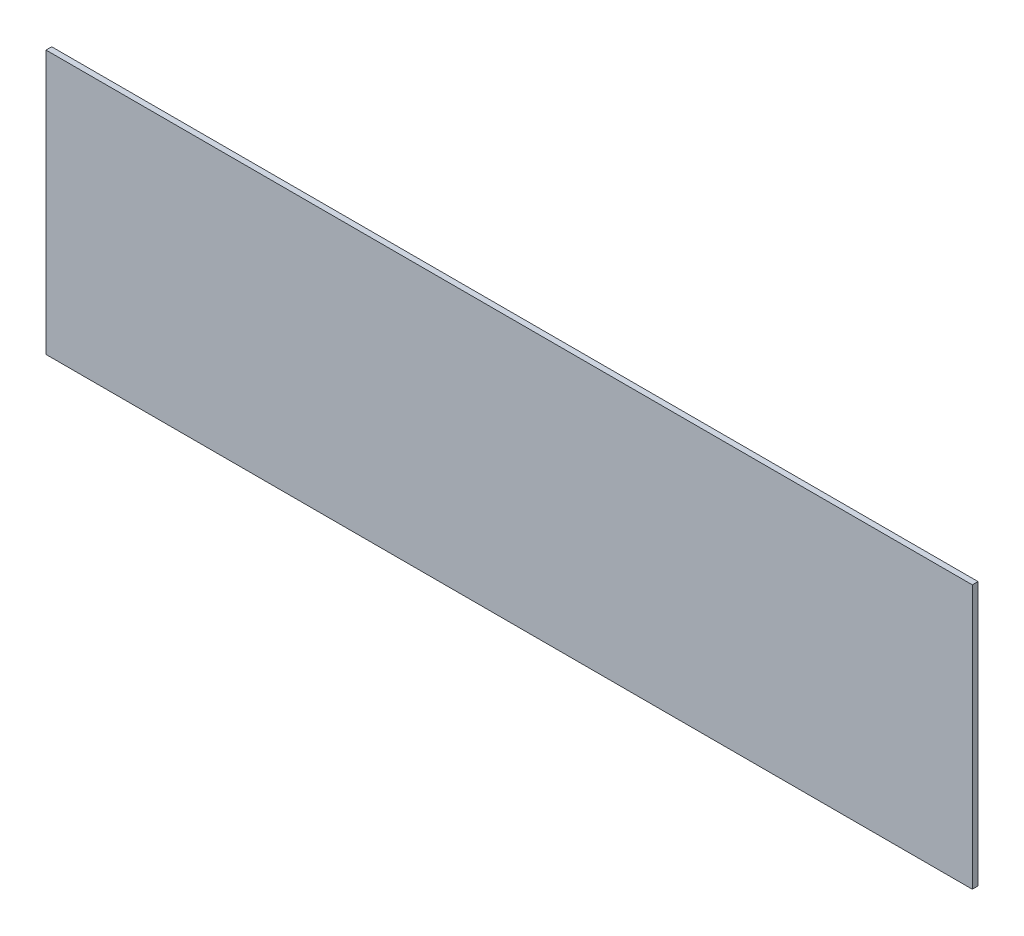
SolidWorks part; units mm, degrees
ref_plane "Front Plane" through (0, 0, 0) normal (0, 0, 1) x (1, 0, 0)
ref_plane "Top Plane" through (0, 0, 0) normal (0, 1, 0) x (1, 0, 0)
ref_plane "Right Plane" through (0, 0, 0) normal (1, 0, 0) x (0, 0, -1)
sketch "Sketch1" plane through (0, 0, 0) normal (0, 0, 1) x (1, 0, 0)
  line L1 (-162.5, -46.25) -> (162.5, -46.25)
  line L2 (-162.5, -46.25) -> (-162.5, 46.25)
  line L3 (-162.5, 46.25) -> (162.5, 46.25)
  line L4 (162.5, -46.25) -> (162.5, 46.25)
  line L5 (-162.5, -46.25) -> (162.5, 46.25) construction
  line L6 (-162.5, 46.25) -> (162.5, -46.25) construction
  point P0 (0, 0)
  dimension "D1" = 325
  dimension "D2" = 92.5
extrude "Boss-Extrude1" add sketch "Sketch1" along normal blind 2
